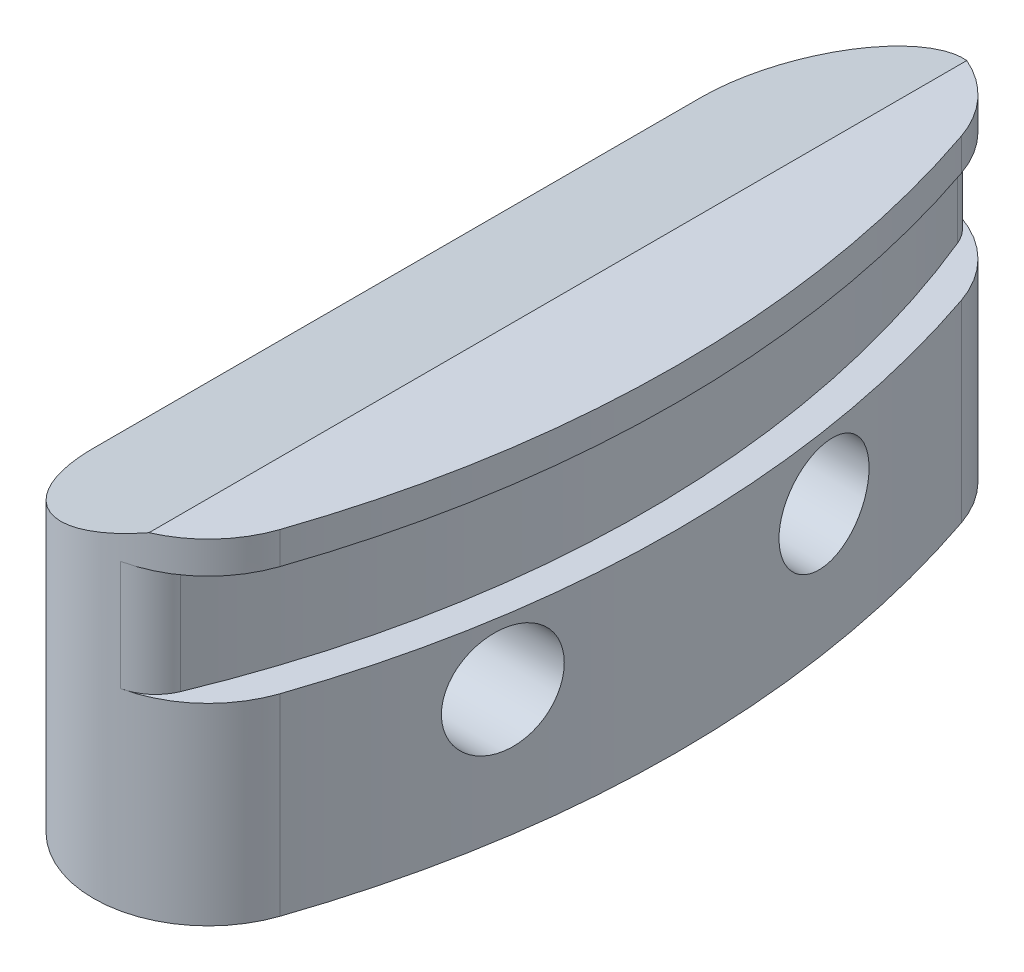
SolidWorks part; units mm, degrees
material "ABS"
ref_plane "Front Plane" through (0, 0, 0) normal (0, 0, 1) x (1, 0, 0)
ref_plane "Top Plane" through (0, 0, 0) normal (0, 1, 0) x (1, 0, 0)
ref_plane "Right Plane" through (0, 0, 0) normal (1, 0, 0) x (0, 0, -1)
sketch "Sketch1" plane through (0, 0, 0) normal (0, 1, 0) x (1, 0, 0)
  line L0 (0, 0) -> (27.9151, -9.525) construction
  line L1 (27.9151, -9.525) -> (27.9151, 9.525) construction
  line L2 (27.9151, 9.525) -> (0, 0) construction
  line L3 (21.4651, -8.4075) -> (21.4651, 8.4075)
  circle A0 centre (0, 0) radius 12.5 construction
  circle A1 centre (0, 0) radius 29.4954 construction
  circle A2 centre (0, 0) radius 38.1 construction
  circle A3 centre (0, 0) radius 29.21 construction
  circle A4 centre (0, 0) radius 22.86 construction
  arc A5 (21.6352, -7.3822) -> (27.645, -9.4328) centre (24.6401, -8.4075) ccw
  arc A6 (21.6352, 7.3822) -> (27.645, 9.4328) centre (24.6401, 8.4075) cw
  circle A11 centre (0, 0) radius 28.3397 construction
  arc A12 (21.6352, 7.3822) -> (21.6352, -7.3822) centre (0, 0) cw
  arc A13 (27.645, 9.4328) -> (27.645, -9.4328) centre (0, 0) cw
  point P8 (21.6352, -7.3822)
  point P9 (27.645, -9.4328)
  point P10 (21.6352, 7.3822)
  point P11 (27.645, 9.4328)
  dimension "D1" = 25
  dimension "D4" = 19.05
  dimension "D5" = 58.42
  dimension "D6" = 6.45
  dimension "D2" = 58.9908
  dimension "D3" = 1.1557
extrude "Boss-Extrude1" add sketch "Sketch1" along normal blind 9.271 contours A13 A6 A12 A5 | A12 A6 L3 A5
sketch "Sketch2" plane through (0, 9.271, 0) normal (0, 1, 0) x (1, 0, 0)
  arc A0 (25.9995, 11.2768) -> (25.9995, -11.2768) centre (0, 0) cw
  arc A1 (27.645, 9.4328) -> (21.6352, 7.3822) centre (24.6401, 8.4075) ccw construction
  circle A2 centre (0, 0) radius 28.3397 construction
  arc A3 (21.6352, -7.3822) -> (27.645, -9.4328) centre (24.6401, -8.4075) ccw construction
  arc A4 (25.9995, -11.2768) -> (27.645, -9.4328) centre (24.6401, -8.4075) ccw
  arc A5 (27.645, -9.4328) -> (27.645, 9.4328) centre (0, 0) ccw
  arc A6 (27.645, 9.4328) -> (25.9995, 11.2768) centre (24.6401, 8.4075) ccw
extrude "Cut-Extrude1" cut sketch "Sketch2" against normal blind 3.937
sketch "Sketch6" plane through (0, 9.271, 0) normal (0, 1, 0) x (1, 0, 0)
  arc A0 (25.9995, -11.2768) -> (25.9995, 11.2768) centre (0, 0) ccw
  arc A1 (27.645, 9.4328) -> (21.6352, 7.3822) centre (24.6401, 8.4075) ccw construction
  circle A2 centre (0, 0) radius 28.3397 construction
  arc A3 (25.9995, -11.2768) -> (27.645, -9.4328) centre (24.6401, -8.4075) ccw
  arc A4 (27.645, -9.4328) -> (27.645, 9.4328) centre (0, 0) ccw
  arc A5 (27.645, 9.4328) -> (25.9995, 11.2768) centre (24.6401, 8.4075) ccw
extrude "Boss-Extrude3" add sketch "Sketch6" against normal blind 0.889
sketch "Sketch7" plane through (21.4651, 0, 0) normal (-1, 0, 0) x (0, 0, 1)
  line L0 (-8.4075, 0) -> (-8.4075, 3.556) construction
  line L1 (-8.4075, 3.556) -> (-4.445, 3.556) construction
  line L2 (-4.445, 3.556) -> (4.445, 3.556) construction
  line L3 (4.445, 3.556) -> (8.4075, 3.556) construction
  line L4 (8.4075, 9.271) -> (8.4075, 0) construction
  line L5 (8.4075, 0) -> (-8.4075, 0) construction
  line L7 (8.4075, 9.271) -> (-8.4075, 9.271) construction
  line L8 (-2.6119, 6.731) -> (-6.2781, 6.731)
  line L9 (-6.2781, 6.731) -> (-8.1112, 3.556)
  line L10 (-8.1112, 3.556) -> (-6.2781, 0.381)
  line L11 (-6.2781, 0.381) -> (-2.6119, 0.381)
  line L12 (-2.6119, 0.381) -> (-0.7788, 3.556)
  line L13 (-0.7788, 3.556) -> (-2.6119, 6.731)
  line L14 (6.2781, 6.731) -> (2.6119, 6.731)
  line L15 (2.6119, 6.731) -> (0.7788, 3.556)
  line L16 (0.7788, 3.556) -> (2.6119, 0.381)
  line L17 (2.6119, 0.381) -> (6.2781, 0.381)
  line L18 (6.2781, 0.381) -> (8.1112, 3.556)
  line L19 (8.1112, 3.556) -> (6.2781, 6.731)
  circle A0 centre (-4.445, 3.556) radius 3.175 construction
  circle A1 centre (4.445, 3.556) radius 3.175 construction
  dimension "D1" = 8.89
  dimension "D2" = 5.715
  dimension "D3" = 6.35
  dimension "D4" = 6.35
hole_wizard "#4 Clearance Hole1" positions "3DSketch1" profile "Sketch8" hole size "#4" standard "ANSI Inch" end condition through all
sketch3d "3DSketch1"
  point P0 (21.4651, 3.556, -4.445)
  point P3 (21.4651, 3.556, 4.445)
sketch "Sketch8" plane through (21.4651, 3.556, -4.445) normal (0, 1, 0) x (0, 0, 1)
  line L0 (0, 0) -> (0, 7.7449)
  line L1 (0, 7.7449) -> (1.4732, 7.7449)
  line L2 (1.4732, 7.7449) -> (1.4732, 0)
  line L5 (1.4732, 0) -> (0, 0)
  line L11 (0, -6.35) -> (0, 107.95) construction
  dimension "Thru Hole Dia." = 2.9464
  dimension "Thru Hole Depth" = 7.7449
fillet "Fillet1" radius 1.27 2 edges at (25.9995, 6.858, 11.2768) (25.9995, 6.858, -11.2768)
extrude "Cut-Extrude2" cut sketch "Sketch7" against normal blind 3.81
sketch "Sketch10" plane through (0, 0, 0) normal (0, 0, 1) x (1, 0, 0)
  line L0 (21.4651, 9.271) -> (21.4651, 7.62)
  line L1 (21.4651, 9.271) -> (21.4651, 0) construction
  line L2 (21.4651, 7.62) -> (25.9101, 9.271)
  line L3 (25.9101, 9.271) -> (21.4651, 9.271)
  dimension "D1" = 1.651
  dimension "D2" = 4.445
extrude "Cut-Extrude3" cut sketch "Sketch10" against normal through all both and the other way through all
